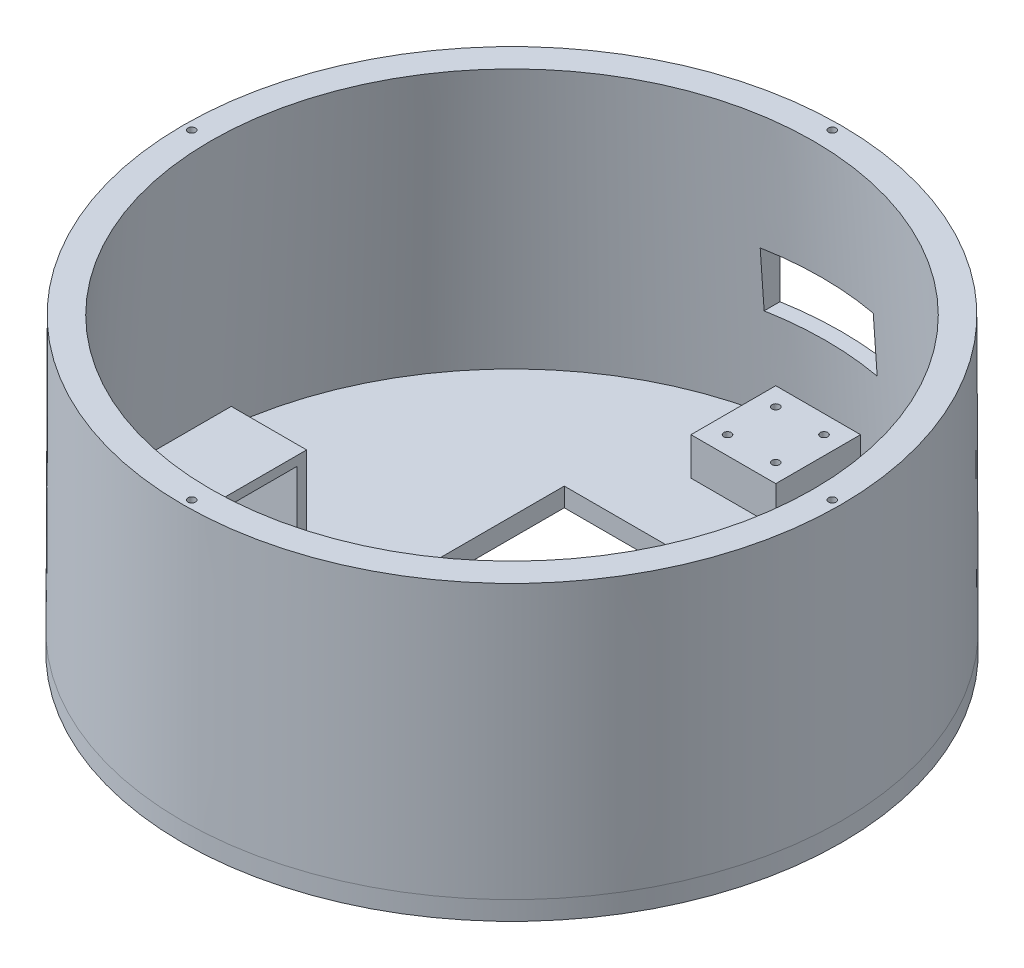
SolidWorks part; units mm, degrees
ref_plane "Front Plane" through (0, 0, 0) normal (0, 0, 1) x (1, 0, 0)
ref_plane "Top Plane" through (0, 0, 0) normal (0, 1, 0) x (1, 0, 0)
ref_plane "Right Plane" through (0, 0, 0) normal (1, 0, 0) x (0, 0, -1)
sketch "Sketch1" plane through (0, 0, 0) normal (0, 1, 0) x (1, 0, 0)
  circle A1 centre (0, 0) radius 175
  dimension "D1" = 350
extrude "Boss-Extrude1" add sketch "Sketch1" against normal blind 10
sketch "Sketch2" plane through (0, 0, 0) normal (0, 1, 0) x (1, 0, 0)
  circle A0 centre (0, 0) radius 175 construction
  circle A1 centre (0, 0) radius 175
  circle A2 centre (0, 0) radius 170
  dimension "D1" = 5
sketch "Sketch3" plane through (0, -10, 0) normal (0, -1, 0) x (1, 0, 0)
  line L0 (-175, 0) -> (175, 0) construction
  line L1 (0, -175) -> (0, 175) construction
  line L2 (175, 0) -> (175, -175) construction
  line L3 (175, 0) -> (175, 175) construction
  line L4 (-175, 0) -> (-175, -175) construction
  line L5 (-175, 0) -> (-175, 175) construction
  line L6 (0, 175) -> (-175, 175) construction
  line L7 (0, 175) -> (175, 175) construction
  line L8 (0, -175) -> (-175, -175) construction
  line L9 (0, -175) -> (175, -175) construction
  line L10 (-87.5, 175) -> (-87.5, -175) construction
  line L11 (87.5, 175) -> (87.5, -175) construction
  line L12 (-175, 87.5) -> (175, 87.5) construction
  line L13 (-175, -87.5) -> (175, -87.5) construction
  line L14 (-175, -175) -> (175, 175) construction
  line L15 (-175, 175) -> (175, -175) construction
  line L16 (-175, -87.5) -> (87.5, 175) construction
  line L17 (-175, 0) -> (0, 175) construction
  line L18 (-175, 87.5) -> (-87.5, 175) construction
  line L19 (-87.5, -175) -> (175, 87.5) construction
  line L20 (0, -175) -> (175, 0) construction
  line L21 (87.5, -175) -> (175, -87.5) construction
  line L22 (-87.5, 175) -> (175, -87.5) construction
  line L23 (0, 175) -> (175, 0) construction
  line L24 (87.5, 175) -> (175, 87.5) construction
  line L25 (-87.5, 0) -> (-92.5, 0) construction
  line L26 (0, -175) -> (-175, 0) construction
  line L27 (-87.5, -175) -> (-175, -87.5) construction
  line L28 (-87.5, 0) -> (-87.5, 21.5052) construction
  line L29 (-127.5, 96.5052) -> (-92.5, 96.5052)
  line L30 (-127.5, 96.5052) -> (-127.5, 21.5052)
  line L31 (-127.5, 21.5052) -> (-92.5, 21.5052)
  line L32 (-92.5, 96.5052) -> (-92.5, 21.5052)
  line L33 (-127.5, 96.5052) -> (-92.5, 21.5052) construction
  line L34 (-127.5, 21.5052) -> (-92.5, 96.5052) construction
  line L36 (127.5, 96.5052) -> (127.5, 21.5052)
  line L37 (127.5, 21.5052) -> (92.5, 21.5052)
  line L38 (92.5, 96.5052) -> (92.5, 21.5052)
  line L39 (127.5, 96.5052) -> (92.5, 96.5052)
  line L45 (-87.5, 21.5052) -> (-92.5, 21.5052) construction
  line L46 (-92.5, 0) -> (-92.5, 21.5052) construction
  line L48 (0, -175) -> (0, -140) construction
  line L51 (-17.5, -122.5) -> (17.5, -122.5)
  line L52 (-17.5, -122.5) -> (-17.5, -157.5)
  line L53 (-17.5, -157.5) -> (17.5, -157.5)
  line L54 (17.5, -122.5) -> (17.5, -157.5)
  line L55 (-17.5, -122.5) -> (17.5, -157.5) construction
  line L56 (-17.5, -157.5) -> (17.5, -122.5) construction
  circle A0 centre (0, 0) radius 175 construction
  point P17 (-110, 59.0052)
  dimension "D1" = 35
  dimension "D2" = 75
  dimension "D3" = 5
  dimension "D5" = 35
  dimension "D6" = 35
extrude "Cut-Extrude1" cut sketch "Sketch3" against normal through all both and the other way through all
sketch "Sketch4" plane through (0, 0, 0) normal (0, 1, 0) x (1, 0, 0)
  line L1 (57.5, -96.5052) -> (57.5, -21.5052)
  line L2 (0, 175) -> (0, -175) construction
  line L3 (0, 175) -> (0, -175)
  line L4 (127.5, -96.5052) -> (127.5, -21.5052)
  line L5 (127.5, -21.5052) -> (92.5, -21.5052)
  line L6 (92.5, -21.5052) -> (92.5, -96.5052)
  line L7 (92.5, -96.5052) -> (127.5, -96.5052)
  line L9 (92.5, -21.5052) -> (57.5, -21.5052)
  line L10 (92.5, -21.5052) -> (92.5, -96.5052)
  line L12 (-92.5, -21.5052) -> (-92.5, -96.5052)
  line L14 (-57.5, -96.5052) -> (-57.5, -21.5052)
  line L15 (-92.5, -21.5052) -> (-57.5, -21.5052)
  line L20 (-92.5, -96.5052) -> (-92.5, -121.5052)
  line L21 (-92.5, -121.5052) -> (-57.5, -121.5052)
  line L22 (-57.5, -96.5052) -> (-57.5, -121.5052)
  line L24 (92.5, -96.5052) -> (92.5, -121.5052)
  line L25 (92.5, -121.5052) -> (57.5, -121.5052)
  line L26 (57.5, -96.5052) -> (57.5, -121.5052)
  dimension "D2" = 25
  dimension "D1" = 0
extrude "Cut-Extrude2" cut sketch "Sketch4" against normal blind 5
sketch "Sketch5" plane through (0, 0, 0) normal (0, 1, 0) x (1, 0, 0)
  line L0 (17.5, 157.5) -> (22.5, 157.5) construction
  line L1 (17.5, 157.5) -> (-17.5, 157.5)
  line L2 (17.5, 157.5) -> (17.5, 122.5)
  line L3 (17.5, 122.5) -> (-17.5, 122.5)
  line L4 (-17.5, 157.5) -> (-17.5, 122.5)
  line L5 (22.5, 157.5) -> (22.5, 162.5) construction
  line L6 (22.5, 162.5) -> (17.5, 162.5) construction
  line L7 (17.5, 162.5) -> (17.5, 157.5) construction
  line L8 (-17.5, 122.5) -> (-22.5, 122.5) construction
  line L9 (-22.5, 122.5) -> (-22.5, 117.5) construction
  line L10 (-22.5, 117.5) -> (-17.5, 117.5) construction
  line L11 (-17.5, 117.5) -> (-17.5, 122.5) construction
  line L13 (22.5, 162.5) -> (-22.5, 162.5)
  line L14 (22.5, 162.5) -> (22.5, 117.5)
  line L15 (22.5, 117.5) -> (-22.5, 117.5)
  line L16 (-22.5, 162.5) -> (-22.5, 117.5)
  dimension "D1" = 5
extrude "Boss-Extrude3" add sketch "Sketch5" along normal blind 15
sketch "Sketch6" plane through (0, 0, 0) normal (0, 1, 0) x (1, 0, 0)
  line L0 (127.5, -21.5052) -> (92.5, -21.5052)
  line L1 (127.5, -21.5052) -> (57.5, -21.5052) construction
  line L2 (92.5, -21.5052) -> (92.5, -16.5052)
  line L3 (92.5, -16.5052) -> (132.5, -16.5052)
  line L4 (132.5, -16.5052) -> (132.5, -101.5052)
  line L5 (132.5, -101.5052) -> (110, -101.5052)
  line L6 (110, -101.5052) -> (110, -96.5052)
  line L7 (92.5, -96.5052) -> (127.5, -96.5052) construction
  line L8 (127.5, -21.5052) -> (127.5, -96.5052)
  line L9 (127.5, -96.5052) -> (110, -96.5052)
  line L10 (0, 0) -> (0, -97.9227) construction
  line L11 (-127.5, -21.5052) -> (-127.5, -96.5052)
  line L12 (-127.5, -21.5052) -> (-92.5, -21.5052)
  line L13 (-92.5, -21.5052) -> (-92.5, -16.5052)
  line L14 (-92.5, -16.5052) -> (-132.5, -16.5052)
  line L15 (-132.5, -16.5052) -> (-132.5, -101.5052)
  line L16 (-132.5, -101.5052) -> (-110, -101.5052)
  line L17 (-110, -101.5052) -> (-110, -96.5052)
  line L18 (-127.5, -96.5052) -> (-110, -96.5052)
  dimension "D1" = 5
  dimension "D2" = 5
  dimension "D3" = 5
  dimension "D4" = 5
extrude "Boss-Extrude4" add sketch "Sketch6" along normal blind 40
sketch "Sketch8" plane through (0, 40, 0) normal (0, 1, 0) x (1, 0, 0)
  line L0 (-97.5, -16.5052) -> (-92.5, -16.5052)
  line L1 (-132.5, -16.5052) -> (-97.5, -16.5052)
  line L2 (-132.5, -16.5052) -> (-132.5, -101.5052)
  line L3 (-132.5, -101.5052) -> (-110, -101.5052)
  line L5 (132.5, -16.5052) -> (97.5, -16.5052)
  line L6 (132.5, -16.5052) -> (132.5, -101.5052)
  line L7 (132.5, -101.5052) -> (110, -101.5052)
  line L9 (-92.5, -16.5052) -> (-92.5, -101.5052)
  line L10 (-92.5, -101.5052) -> (-110, -101.5052)
  line L11 (97.5, -16.5052) -> (92.5, -16.5052)
  line L12 (92.5, -16.5052) -> (92.5, -101.5052)
  line L13 (92.5, -96.5052) -> (92.5, -121.5052) construction
  line L14 (92.5, -101.5052) -> (110, -101.5052)
  line L15 (-132.5, -16.5052) -> (-132.5, -101.5052) construction
extrude "Boss-Extrude6" add sketch "Sketch8" along normal blind 5
sketch "Sketch9" plane through (0, 15, 0) normal (0, 1, 0) x (1, 0, 0)
  line L1 (22.5, 162.5) -> (-22.5, 162.5)
  line L2 (22.5, 162.5) -> (22.5, 117.5)
  line L3 (22.5, 117.5) -> (-22.5, 117.5)
  line L4 (-22.5, 162.5) -> (-22.5, 117.5)
extrude "Boss-Extrude7" add sketch "Sketch9" along normal blind 5
sketch "Sketch10" plane through (0, 0, 0) normal (0, 1, 0) x (1, 0, 0)
  line L0 (-65, -21.5052) -> (-65, 117.5) construction
  line L4 (-17.5, 122.5) -> (17.5, 122.5)
  line L5 (17.5, 122.5) -> (17.5, 157.5)
  line L6 (17.5, 157.5) -> (-17.5, 157.5)
  line L7 (-17.5, 157.5) -> (-17.5, 122.5)
  line L8 (-17.5, 122.5) -> (17.5, 122.5)
  line L9 (17.5, 122.5) -> (17.5, 157.5)
  line L10 (17.5, 157.5) -> (-17.5, 157.5)
  line L11 (-17.5, 157.5) -> (-17.5, 122.5)
  line L12 (127.5, -96.5052) -> (127.5, -21.5052)
  line L13 (127.5, -21.5052) -> (92.5, -21.5052)
  line L14 (92.5, -21.5052) -> (92.5, -96.5052)
  line L15 (92.5, -96.5052) -> (127.5, -96.5052)
  line L16 (127.5, -96.5052) -> (127.5, -21.5052)
  line L17 (127.5, -21.5052) -> (92.5, -21.5052)
  line L18 (92.5, -21.5052) -> (92.5, -96.5052)
  line L19 (92.5, -96.5052) -> (127.5, -96.5052)
  line L20 (-92.5, -96.5052) -> (-92.5, -21.5052)
  line L21 (-127.5, -96.5052) -> (-92.5, -96.5052)
  line L22 (-127.5, -21.5052) -> (-127.5, -96.5052)
  line L23 (-92.5, -21.5052) -> (-127.5, -21.5052)
  line L24 (-92.5, -96.5052) -> (-92.5, -21.5052)
  line L25 (-127.5, -96.5052) -> (-92.5, -96.5052)
  line L26 (-127.5, -21.5052) -> (-127.5, -96.5052)
  line L27 (-92.5, -21.5052) -> (-127.5, -21.5052)
  line L32 (-65, 117.5) -> (65, 117.5) construction
  line L33 (65, 117.5) -> (65, -21.5052) construction
  line L39 (65, -21.5052) -> (-65, -21.5052) construction
  line L40 (0, 27.9974) -> (0, -21.5052) construction
  line L41 (-65, 67.9974) -> (65, 67.9974)
  line L42 (-65, 67.9974) -> (-65, 27.9974)
  line L43 (-65, 27.9974) -> (65, 27.9974)
  line L44 (22.5, 117.5) -> (22.5, 162.5)
  line L45 (22.5, 162.5) -> (-22.5, 162.5)
  line L46 (-22.5, 162.5) -> (-22.5, 117.5)
  line L47 (-22.5, 117.5) -> (22.5, 117.5)
  line L48 (22.5, 117.5) -> (22.5, 162.5)
  line L49 (22.5, 162.5) -> (-22.5, 162.5)
  line L50 (-22.5, 162.5) -> (-22.5, 117.5)
  line L51 (-22.5, 117.5) -> (22.5, 117.5)
  line L52 (65, 67.9974) -> (65, 27.9974)
  line L53 (-65, 67.9974) -> (65, 27.9974) construction
  line L54 (-65, 27.9974) -> (65, 67.9974) construction
  line L55 (0, 67.9974) -> (0, 117.5) construction
  line L56 (-92.5, -21.5052) -> (-57.5, -21.5052) construction
  point P22 (0, 47.9974)
  dimension "D4" = 0
  dimension "D5" = 40
  dimension "D6" = 130
  dimension "D1" = 0
  dimension "D2" = 0
  dimension "D3" = 0
extrude "Cut-Extrude5" [suppressed] cut sketch "Sketch10" against normal through all both and the other way through all
sketch "Face1" [suppressed] plane through (0, 0, 0) normal (0, 1, 0) x (1, 0, 0)
  line L1 (-65, 46.25) -> (65, 46.25)
  line L2 (-65, 46.25) -> (-65, 6.25)
  line L3 (-65, 6.25) -> (65, 6.25)
  line L4 (65, 46.25) -> (65, 6.25)
ref_plane "Plane1" [suppressed] through (0, 0, 0) normal (1, 0, 0) x (0, 0, -1)
ref_plane "Plane2" [suppressed] through (0, 0, 17.3) normal (0, 0, 1) x (1, 0, 0)
sketch "Sketch36" plane through (0, 0, 0) normal (0, 1, 0) x (1, 0, 0)
  line L0 (-57.5, -21.5052) -> (-57.5, -121.5052) construction
  line L1 (-52.5, -80.2552) -> (52.5, -80.2552)
  line L2 (-52.5, -80.2552) -> (-52.5, 80.2552)
  line L3 (-52.5, 80.2552) -> (52.5, 80.2552)
  line L4 (52.5, -80.2552) -> (52.5, 80.2552)
  line L5 (-52.5, -80.2552) -> (52.5, 80.2552) construction
  line L6 (-52.5, 80.2552) -> (52.5, -80.2552) construction
  line L7 (57.5, -121.5052) -> (57.5, -21.5052) construction
  line L8 (-92.5, -59.0052) -> (92.5, -59.0052) construction
  line L13 (92.5, -16.5052) -> (92.5, -101.5052) construction
  line L14 (92.5, -16.5052) -> (92.5, -101.5052)
  line L17 (-132.5, -16.5052) -> (-132.5, -101.5052)
  line L18 (-132.5, -101.5052) -> (-92.5, -101.5052)
  line L19 (-92.5, -101.5052) -> (-92.5, -16.5052)
  line L20 (-92.5, -16.5052) -> (-132.5, -16.5052)
  line L23 (-92.5, -101.5052) -> (-92.5, -16.5052)
  point P0 (0, 0)
  dimension "D1" = 5
  dimension "D2" = 5
  dimension "D3" = 0
  dimension "D4" = 21.25
extrude "Cut-Extrude14" cut sketch "Sketch36" against normal through all both and the other way through all contours L1 L4 L3 L2
sketch "Sketch37" plane through (0, 0, 0) normal (0, 1, 0) x (1, 0, 0)
  line L0 (0, 0) -> (0, -80.2552) construction
  line L1 (-52.5, -80.2552) -> (-31.25, -80.2552) construction
  line L2 (-31.25, -80.2552) -> (-28.75, -80.2552)
  line L3 (-28.75, -80.2552) -> (-28.75, -77.7552)
  line L4 (-28.75, -77.7552) -> (-23.75, -77.7552)
  line L5 (-23.75, -77.7552) -> (-23.75, -80.2552)
  line L6 (-23.75, -80.2552) -> (-21.25, -80.2552)
  line L7 (-21.25, -80.2552) -> (-21.25, -87.7552)
  line L8 (-21.25, -87.7552) -> (-31.25, -87.7552)
  line L9 (-31.25, -87.7552) -> (-31.25, -80.2552)
  line L10 (0, 0) -> (0, 80.2552) construction
  line L11 (-52.5, 80.2552) -> (52.5, 80.2552) construction
  line L12 (0, 0) -> (52.5, 0) construction
  line L13 (52.5, -80.2552) -> (52.5, 80.2552) construction
  line L14 (-52.5, -80.2552) -> (52.5, -80.2552) construction
  line L15 (0, -80.2552) -> (-21.25, -80.2552) construction
  line L16 (31.25, -87.7552) -> (31.25, -80.2552)
  line L17 (21.25, -87.7552) -> (31.25, -87.7552)
  line L18 (21.25, -80.2552) -> (21.25, -87.7552)
  line L19 (23.75, -80.2552) -> (21.25, -80.2552)
  line L20 (23.75, -77.7552) -> (23.75, -80.2552)
  line L21 (28.75, -77.7552) -> (23.75, -77.7552)
  line L22 (28.75, -80.2552) -> (28.75, -77.7552)
  line L23 (31.25, -80.2552) -> (28.75, -80.2552)
  line L24 (31.25, 80.2552) -> (28.75, 80.2552)
  line L25 (28.75, 80.2552) -> (28.75, 77.7552)
  line L26 (28.75, 77.7552) -> (23.75, 77.7552)
  line L27 (23.75, 77.7552) -> (23.75, 80.2552)
  line L28 (23.75, 80.2552) -> (21.25, 80.2552)
  line L29 (21.25, 80.2552) -> (21.25, 87.7552)
  line L30 (21.25, 87.7552) -> (31.25, 87.7552)
  line L31 (31.25, 87.7552) -> (31.25, 80.2552)
  line L32 (-31.25, 87.7552) -> (-31.25, 80.2552)
  line L33 (-21.25, 87.7552) -> (-31.25, 87.7552)
  line L34 (-21.25, 80.2552) -> (-21.25, 87.7552)
  line L35 (-23.75, 80.2552) -> (-21.25, 80.2552)
  line L36 (-23.75, 77.7552) -> (-23.75, 80.2552)
  line L37 (-28.75, 77.7552) -> (-23.75, 77.7552)
  line L38 (-28.75, 80.2552) -> (-28.75, 77.7552)
  line L39 (-31.25, 80.2552) -> (-28.75, 80.2552)
  dimension "D1" = 2.5
  dimension "D2" = 7.5
  dimension "D4" = 2.5
  dimension "D5" = 5
extrude "Boss-Extrude11" [suppressed] add sketch "Sketch37" along normal blind 50
sketch "Sketch42" plane through (0, -5, 0) normal (0, 1, 0) x (1, 0, 0)
  line L0 (-92.5, -21.5052) -> (-57.5, -21.5052) construction
  line L1 (-57.5, -21.5052) -> (-57.5, -121.5052) construction
  line L2 (-57.5, -121.5052) -> (-92.5, -121.5052) construction
  line L3 (-92.5, -121.5052) -> (-92.5, -21.5052) construction
  line L4 (-75, -71.5052) -> (-57.5, -71.5052) construction
  line L5 (-57.5, -71.5052) -> (-75, -96.5052) construction
  line L6 (-75, -96.5052) -> (-57.5, -121.5052) construction
  line L7 (-75, -71.5052) -> (-75, -96.5052) construction
  line L8 (-75, -96.5052) -> (-75, -121.5052) construction
  line L9 (-66.25, -84.0052) -> (-66.25, -64.0052) construction
  line L10 (-66.25, -64.0052) -> (-61.25, -64.0052) construction
  line L11 (-61.25, -64.0052) -> (-61.25, -84.0052) construction
  line L12 (-61.25, -84.0052) -> (-66.25, -84.0052) construction
  line L13 (-66.25, -64.0052) -> (-61.25, -64.0052)
  line L14 (-61.25, -64.0052) -> (-61.25, -84.0052)
  line L15 (-61.25, -84.0052) -> (-66.25, -84.0052)
  line L16 (-66.25, -84.0052) -> (-66.25, -64.0052)
  line L17 (0, 0) -> (0, -80.2552) construction
  line L18 (-52.5, -80.2552) -> (52.5, -80.2552) construction
  line L19 (61.25, -84.0052) -> (66.25, -84.0052)
  line L20 (61.25, -64.0052) -> (61.25, -84.0052)
  line L21 (66.25, -64.0052) -> (61.25, -64.0052)
  line L22 (66.25, -84.0052) -> (66.25, -64.0052)
  dimension "D1" = 20
  dimension "D2" = 5
extrude "Cut-Extrude16" [suppressed] cut sketch "Sketch42" against normal through all both and the other way through all
sketch "Sketch43" [suppressed] plane through (0, -10, 0) normal (0, -1, 0) x (1, 0, 0)
  line L0 (-52.5, -80.2552) -> (52.5, -80.2552) construction
  line L1 (-52.5, 80.2552) -> (52.5, 80.2552) construction
  line L2 (52.5, 80.2552) -> (52.5, -80.2552) construction
  line L3 (-52.5, 80.2552) -> (-52.5, -80.2552) construction
  line L4 (-52.5, -80.2552) -> (52.5, -80.2552)
  line L5 (-52.5, 80.2552) -> (52.5, 80.2552)
  line L6 (52.5, 45.6276) -> (52.5, 34.6276)
  line L7 (-52.5, 80.2552) -> (-52.5, 45.6276)
  line L8 (52.5, 0) -> (0, 0) construction
  line L9 (0, 0) -> (0, 80.2552) construction
  line L10 (52.5, 34.6276) -> (75, 34.6276)
  line L11 (52.5, 34.6276) -> (52.5, 45.6276)
  line L12 (52.5, 45.6276) -> (75, 45.6276)
  line L13 (75, 34.6276) -> (75, 45.6276)
  line L14 (52.5, 80.2552) -> (52.5, 45.6276) construction
  line L15 (52.5, 34.6276) -> (52.5, 0) construction
  line L16 (52.5, 0) -> (52.5, -80.2552)
  line L17 (52.5, -45.6276) -> (75, -45.6276)
  line L18 (75, -34.6276) -> (75, -45.6276)
  line L19 (52.5, -34.6276) -> (75, -34.6276)
  line L20 (52.5, -34.6276) -> (52.5, -45.6276)
  line L21 (-52.5, -34.6276) -> (-52.5, -45.6276)
  line L22 (-52.5, -34.6276) -> (-75, -34.6276)
  line L23 (-75, -34.6276) -> (-75, -45.6276)
  line L24 (-52.5, -45.6276) -> (-75, -45.6276)
  line L29 (-52.5, 34.6276) -> (-52.5, -80.2552)
  line L30 (10.5, 80.2552) -> (10.5, 122.7552)
  line L31 (10.5, 122.7552) -> (-10.5, 122.7552)
  line L32 (-10.5, 122.7552) -> (-10.5, 80.2552)
  line L33 (-10.5, 80.2552) -> (10.5, 80.2552)
  line L34 (10.5, 101.5052) -> (23.75, 101.5052) construction
  line L35 (23.75, 101.5052) -> (23.75, 80.2552) construction
  line L36 (-10.5, 101.5052) -> (-23.75, 101.5052) construction
  line L37 (-23.75, 101.5052) -> (-23.75, 80.2552) construction
  dimension "D1" = 22.5
  dimension "D2" = 11
  dimension "D3" = 21
  dimension "D4" = 42.5
extrude "Cut-Extrude17" [suppressed] cut sketch "Sketch43" against normal blind 7.5 contours L21 L24 L23 L22 | L17 L18 L19 L20 | L33 L30 L31 L32
sketch "Sketch44" [suppressed] plane through (0, -10, 0) normal (0, -1, 0) x (1, 0, 0)
  line L0 (-10.5, 122.7552) -> (-10.5, 80.2552) construction
  line L1 (10.5, 80.2552) -> (10.5, 122.7552) construction
  line L2 (52.5, -45.6276) -> (75, -45.6276) construction
  line L3 (52.5, -34.6276) -> (75, -34.6276) construction
  line L4 (-52.5, -45.6276) -> (-75, -45.6276) construction
  line L5 (-52.5, -34.6276) -> (-75, -34.6276) construction
  line L6 (-10.5, 122.7552) -> (-10.5, 80.2552)
  line L7 (10.5, 80.2552) -> (10.5, 122.7552)
  line L8 (52.5, -45.6276) -> (75, -45.6276)
  line L9 (52.5, -34.6276) -> (75, -34.6276)
  line L10 (-52.5, -45.6276) -> (-75, -45.6276)
  line L11 (-52.5, -34.6276) -> (-75, -34.6276)
  line L12 (-75, -34.6276) -> (-75, -37.6276)
  line L13 (-75, -34.6276) -> (-75, -45.6276) construction
  line L14 (-75, -37.6276) -> (-52.5, -37.6276)
  line L15 (-52.5, -34.6276) -> (-52.5, -45.6276) construction
  line L16 (-52.5, -37.6276) -> (-52.5, -34.6276)
  line L17 (-75, -45.6276) -> (-75, -42.6276)
  line L18 (-75, -42.6276) -> (-52.5, -42.6276)
  line L19 (-52.5, -42.6276) -> (-52.5, -45.6276)
  line L20 (75, -34.6276) -> (75, -37.6276)
  line L21 (75, -34.6276) -> (75, -45.6276) construction
  line L22 (75, -37.6276) -> (52.5, -37.6276)
  line L23 (52.5, -34.6276) -> (52.5, -45.6276) construction
  line L24 (52.5, -37.6276) -> (52.5, -34.6276)
  line L25 (52.5, -45.6276) -> (52.5, -42.6276)
  line L26 (52.5, -42.6276) -> (75, -42.6276)
  line L27 (75, -42.6276) -> (75, -45.6276)
  line L28 (-10.5, 122.7552) -> (-4.5, 122.7552)
  line L29 (10.5, 122.7552) -> (-10.5, 122.7552) construction
  line L30 (-4.5, 122.7552) -> (-4.5, 80.2552)
  line L31 (-10.5, 80.2552) -> (10.5, 80.2552) construction
  line L32 (-4.5, 80.2552) -> (-10.5, 80.2552)
  line L33 (10.5, 122.7552) -> (4.5, 122.7552)
  line L34 (10.5, 122.7552) -> (-10.5, 122.7552) construction
  line L35 (4.5, 122.7552) -> (4.5, 80.2552)
  line L36 (4.5, 80.2552) -> (10.5, 80.2552)
  line L38 (-75, -37.6276) -> (-72, -37.6276)
  line L39 (-75, -37.6276) -> (-75, -42.6276)
  line L40 (-75, -42.6276) -> (-72, -42.6276)
  line L41 (-72, -37.6276) -> (-72, -42.6276)
  line L42 (75, -37.6276) -> (72, -37.6276)
  line L43 (75, -37.6276) -> (75, -42.6276)
  line L44 (75, -42.6276) -> (72, -42.6276)
  line L45 (72, -37.6276) -> (72, -42.6276)
  line L46 (-4.5, 122.7552) -> (4.5, 122.7552)
  line L47 (-4.5, 122.7552) -> (-4.5, 116.7552)
  line L48 (-4.5, 116.7552) -> (4.5, 116.7552)
  line L49 (4.5, 122.7552) -> (4.5, 116.7552)
  line M9 (-75, -45.6276) -> (-75, -34.6276)
  line M10 (-75, -34.6276) -> (-52.5, -34.6276)
  line M13 (-10.5, 80.2552) -> (-10.5, 122.7552)
  line M14 (-10.5, 122.7552) -> (10.5, 122.7552)
  line M15 (10.5, 122.7552) -> (10.5, 80.2552)
  line M18 (52.5, -34.6276) -> (75, -34.6276)
  line M19 (75, -34.6276) -> (75, -45.6276)
  line M20 (75, -45.6276) -> (52.5, -45.6276)
  line M24 (-52.5, -45.6276) -> (-75, -45.6276)
  dimension "D1" = 3
  dimension "D2" = 6
  dimension "D3" = 3
  dimension "D4" = 3
  dimension "D5" = 6
extrude "Boss-Extrude13" [suppressed] add sketch "Sketch44" against normal blind 2.5 contours L24 L22 M19 M18 | L26 L25 M20 M19 | L22 L45 L26 M19 | L41 L14 L18 M9 | L19 L18 M9 M24 | L14 L16 M10 M9 | L32 L30 M14 M13 | L30 L48 L35 M14 | L35 L36 M15 M14
sketch "Sketch45" plane through (0, -5, 0) normal (0, 1, 0) x (1, 0, 0)
  line L0 (92.5, -21.5052) -> (92.5, -96.5052) construction
  line L1 (92.5, -21.5052) -> (92.5, -96.5052)
  line L2 (92.5, -59.0052) -> (57.5, -59.0052) construction
  line L3 (57.5, -121.5052) -> (57.5, -21.5052) construction
  line L4 (73.7, -59.0052) -> (73.7, -64.5052) construction
  line L5 (73.7, -64.5052) -> (68.7, -64.5052) construction
  line L6 (0, 0) -> (0, -80.2552) construction
  line L7 (73.7, -64.5052) -> (68.7, -64.5052)
  line L8 (73.7, -64.5052) -> (73.7, -88.5052)
  line L9 (73.7, -88.5052) -> (68.7, -88.5052)
  line L10 (68.7, -64.5052) -> (68.7, -88.5052)
  line L11 (-52.5, -80.2552) -> (52.5, -80.2552) construction
  line L12 (-73.7, -88.5052) -> (-68.7, -88.5052)
  line L13 (-68.7, -64.5052) -> (-68.7, -88.5052)
  line L14 (-73.7, -64.5052) -> (-68.7, -64.5052)
  line L15 (-73.7, -64.5052) -> (-73.7, -88.5052)
  dimension "D1" = 5
  dimension "D2" = 18.8
  dimension "D3" = 5.5
  dimension "D4" = 24
extrude "Boss-Extrude14" add sketch "Sketch45" along normal blind 25 contours L7 L10 L9 L8 | L14 L15 L12 L13
sketch "Sketch46" plane through (68.7, 0, 0) normal (-1, 0, 0) x (0, 0, 1)
  line L0 (64.5052, 20) -> (64.5052, -5) construction
  line L1 (64.5052, -5) -> (88.5052, -5) construction
  line L2 (88.5052, -5) -> (88.5052, 20) construction
  line L3 (88.5052, 20) -> (64.5052, 20) construction
  line L4 (64.5052, 20) -> (88.5052, -5) construction
  line L5 (88.5052, 20) -> (64.5052, -5) construction
  line L6 (64.5052, 7.5) -> (70.0052, 7.5) construction
  line L7 (68.0052, 7.5) -> (68.1052, 7.5)
  line L8 (72.0052, 7.5) -> (71.9052, 7.5)
  line L9 (79.5052, -2.2) -> (79.5052, 14.8) construction
  line L10 (79.5052, 6.3) -> (81.8414, 6.3) construction
  arc A0 (68.1052, 7.5) -> (71.9052, 7.5) centre (70.0052, 7.5) ccw
  arc A1 (72.0052, 7.5) -> (68.0052, 7.5) centre (70.0052, 7.5) ccw
  circle A2 centre (79.5052, -2.2) radius 1.7
  circle A3 centre (79.5052, 14.8) radius 1.7
  dimension "D2" = 3.8
  dimension "D3" = 4
  dimension "D5" = 3.4
  dimension "D1" = 5.5
  dimension "D4" = 2.8
  dimension "D6" = 9
  dimension "D7" = 17
extrude "Cut-Extrude18" cut sketch "Sketch46" against normal blind 25
ref_plane "Plane4" through (0, 0, 0) normal (-1, 0, 0) x (0, 0, 1)
mirror "Mirror1" about plane through (0, 0, 0) normal (-1, 0, 0) of "Cut-Extrude18"
ref_plane "Plane5" [suppressed] through (0, 0, -102.6276) normal (0, 0, 1) x (1, 0, 0)
sketch "Sketch49" plane through (0, 20, 0) normal (0, 1, 0) x (1, 0, 0)
  line L0 (-22.5, 117.5) -> (22.5, 162.5) construction
  line L1 (-22.5, 162.5) -> (22.5, 117.5) construction
  line L2 (0, 155) -> (0, 125) construction
  line L3 (-15, 125) -> (15, 125)
  line L4 (22.5, 117.5) -> (22.5, 162.5)
  line L5 (22.5, 162.5) -> (-22.5, 162.5)
  line L6 (-22.5, 162.5) -> (-22.5, 117.5)
  line L7 (-22.5, 117.5) -> (22.5, 117.5)
  line L8 (22.5, 117.5) -> (22.5, 162.5)
  line L9 (22.5, 162.5) -> (-22.5, 162.5)
  line L10 (-22.5, 162.5) -> (-22.5, 117.5)
  line L11 (-22.5, 117.5) -> (22.5, 117.5)
  line L12 (-15, 125) -> (-15, 155)
  line L13 (-15, 155) -> (15, 155)
  line L14 (15, 125) -> (15, 155)
  line L15 (-15, 125) -> (15, 155) construction
  line L16 (-15, 155) -> (15, 125) construction
  line L17 (-15, 140) -> (15, 140) construction
  line L18 (-15, 155) -> (-12.8033, 152.8033)
  line L19 (-12.8033, 152.8033) -> (-10.6066, 150.6066)
  circle A0 centre (0, 140) radius 15
  circle A1 centre (-12.8033, 152.8033) radius 2
  circle A2 centre (-12.8033, 127.1967) radius 2
  circle A3 centre (12.8033, 127.1967) radius 2
  circle A4 centre (12.8033, 152.8033) radius 2
  dimension "D2" = 30
  dimension "D3" = 4
  dimension "D1" = 0
extrude "Cut-Extrude20" cut sketch "Sketch49" against normal through all contours L19 A1 L18 | L18 A1 L19 | A4 | A2 | A3
ref_plane "Plane6" through (0, 0, 0) normal (0, 0, 1) x (1, 0, 0)
sketch "Sketch51" plane through (0, 0, 0) normal (0, 0, 1) x (1, 0, 0)
  line L0 (-160, 145) -> (-170, 0)
  line L1 (-160, 145) -> (-174.5, 145)
  line L2 (0, 0) -> (0, 68.2321) construction
  line L3 (175, 0) -> (-175, 0)
  line L4 (-170, 0) -> (-175, 0)
  line L5 (-160, 145) -> (-174.5, 145)
  line L6 (-175, 145) -> (-175, 0) construction
  line L7 (-174.5, 145) -> (-175, 145) construction
  line L8 (-174.5, 145) -> (-175, 0)
  dimension "D5" = 0.5
  dimension "D1" = 15
  dimension "D3" = 5
  dimension "D4" = 145
  dimension "D2" = 0
revolve "Revolve1" add sketch "Sketch51" angle 360 about L2
sketch "Sketch52" plane through (0, 145, 0) normal (0, 1, 0) x (1, 0, 0)
  circle A0 centre (0, 0) radius 170 construction
  circle A1 centre (0, 0) radius 175 construction
  circle A2 centre (0, 0) radius 170
  circle A3 centre (0, 0) radius 175
sketch "Sketch48" [suppressed] plane through (0, 0, -102.6276) normal (0, 0, 1) x (1, 0, 0)
  line L0 (-22.5, 20) -> (-22.5, 50) construction
  line L1 (-22.5, 50) -> (22.5, 50) construction
  line L2 (22.5, 50) -> (22.5, 20) construction
  line L3 (-22.5, 50) -> (-30, 50) construction
  line L4 (-22.5, 0) -> (22.5, 0)
  line L5 (22.5, 0) -> (22.5, 20)
  line L6 (22.5, 20) -> (-22.5, 20)
  line L7 (-22.5, 20) -> (-22.5, 0)
  line L9 (22.5, 0) -> (22.5, 20)
  line L10 (22.5, 20) -> (-22.5, 20)
  line L11 (-22.5, 20) -> (-22.5, 0)
  line L12 (-30, 50) -> (-30, 80) construction
  line L13 (-30, 80) -> (30, 80) construction
  line L14 (30, 80) -> (30, 50) construction
  line L15 (30, 50) -> (22.5, 50) construction
  line L17 (-30, 80) -> (30, 80)
  line L18 (-30, 80) -> (-30, 50)
  line L19 (-30, 50) -> (30, 50)
  line L20 (30, 80) -> (30, 50)
  dimension "D2" = 30
  dimension "D3" = 60
  dimension "D4" = 30
  dimension "D1" = 0
extrude "Cut-Extrude19" [suppressed] cut sketch "Sketch48" against normal through all contours L20 L17 L18 L19
sketch "Sketch57" plane through (0, 145, 0) normal (0, 1, 0) x (1, 0, 0)
  line L0 (0, 0) -> (165, 0) construction
  line L1 (165, 0) -> (168, 0) construction
  line L2 (172, 0) -> (175, 0) construction
  line L3 (168, 0) -> (170, 0) construction
  line L4 (170, 0) -> (172, 0) construction
  line L5 (0, 0) -> (0, 165) construction
  line L6 (0, 165) -> (0, 168) construction
  line L7 (0, 172) -> (0, 175) construction
  circle A2 centre (170, 0) radius 2
  circle A3 centre (-170, 0) radius 2
  circle A4 centre (0, 170) radius 2
  circle A5 centre (0, -170) radius 2
  dimension "D1" = 165
  dimension "D2" = 3
  dimension "D3" = 4
  dimension "D4" = 4
  dimension "D5" = 3
  dimension "D6" = 165
  dimension "D7" = 165
  dimension "D8" = 3
extrude "Cut-Extrude24" cut sketch "Sketch57" against normal blind 5.5
sketch "Sketch58" plane through (0, 0, -117.5) normal (0, 0, 1) x (1, 0, 0)
  line L0 (-30, 65) -> (-174.7759, 65) construction
  line L1 (-30, 50) -> (30, 50)
  line L2 (-30, 50) -> (-30, 80)
  line L3 (-30, 80) -> (30, 80)
  line L4 (30, 50) -> (30, 80)
  line L5 (-174.5, 145) -> (-175, 0) construction
  line L6 (30, 65) -> (174.7759, 65) construction
  line L7 (175, 0) -> (174.5, 145) construction
  dimension "D1" = 65
  dimension "D2" = 60
  dimension "D3" = 30
extrude "Cut-Extrude25" cut sketch "Sketch58" against normal through all
